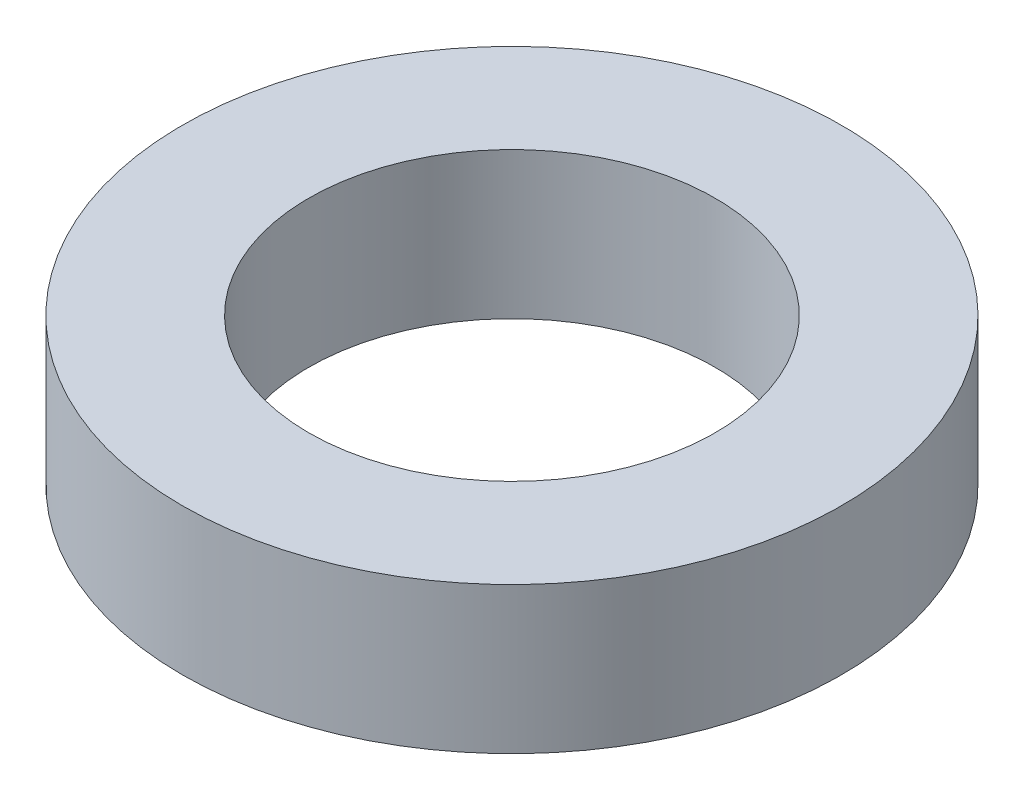
SolidWorks part; units mm, degrees
ref_plane "Front Plane" through (0, 0, 0) normal (0, 0, 1) x (1, 0, 0)
ref_plane "Top Plane" through (0, 0, 0) normal (0, 1, 0) x (1, 0, 0)
ref_plane "Right Plane" through (0, 0, 0) normal (1, 0, 0) x (0, 0, -1)
sketch "Sketch1" plane through (0, 0, 0) normal (0, 1, 0) x (1, 0, 0)
  circle A0 centre (0, 0) radius 13.875
  circle A1 centre (0, 0) radius 22.5
  dimension "D1" = 27.75
  dimension "D2" = 45
extrude "Boss-Extrude1" add sketch "Sketch1" along normal blind 10
